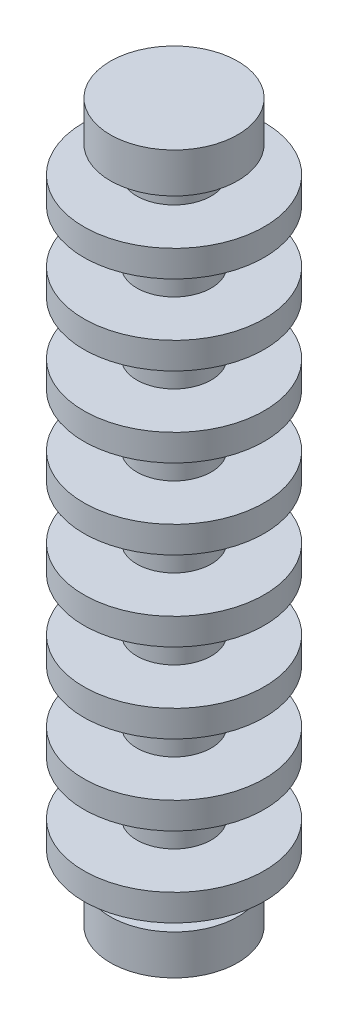
SolidWorks part; units mm, degrees
ref_plane "Front Plane" through (0, 0, 0) normal (0, 0, 1) x (1, 0, 0)
ref_plane "Top Plane" through (0, 0, 0) normal (0, 1, 0) x (1, 0, 0)
ref_plane "Right Plane" through (0, 0, 0) normal (1, 0, 0) x (0, 0, -1)
sketch "Sketch1" plane through (0, 0, 0) normal (0, 0, 1) x (1, 0, 0)
  line L0 (0, -24) -> (0, 24) construction
  line L1 (2.8, 24) -> (2.8, 22)
  line L2 (-20.9325, 24) -> (2.8, 24) construction
  line L3 (2.8, 18) -> (2.8, 16)
  line L4 (2.8, 16) -> (6.8, 16)
  line L5 (2.8, 22) -> (6.8, 22)
  line L6 (6.8, 22) -> (6.8, 20)
  line L7 (6.8, 20) -> (2.8, 20)
  line L8 (2.8, 20) -> (2.8, 18)
  line L9 (2.8, 24) -> (4.8, 24)
  line L10 (4.8, 24) -> (4.8, 27)
  line L11 (4.8, 27) -> (0, 27)
  line L12 (0, 0) -> (33.9437, 0) construction
  line L13 (6.8, 16) -> (6.8, 14)
  line L14 (6.8, 14) -> (2.8, 14)
  line L15 (2.8, 14) -> (2.8, 12)
  line L16 (0, 27) -> (0, -27)
  line L17 (4.8, -27) -> (0, -27)
  line L18 (4.8, -24) -> (4.8, -27)
  line L19 (2.8, -24) -> (4.8, -24)
  line L20 (2.8, 12) -> (2.8, 10)
  line L21 (2.8, 10) -> (6.8, 10)
  line L22 (6.8, 10) -> (6.8, 8)
  line L23 (6.8, 8) -> (2.8, 8)
  line L24 (2.8, 8) -> (2.8, 6)
  line L29 (2.8, 6) -> (2.8, 4)
  line L30 (2.8, 4) -> (6.8, 4)
  line L31 (6.8, 4) -> (6.8, 2)
  line L32 (6.8, 2) -> (2.8, 2)
  line L33 (2.8, 2) -> (2.8, 0)
  line L38 (2.8, 0) -> (2.8, -2)
  line L39 (2.8, -2) -> (6.8, -2)
  line L40 (6.8, -2) -> (6.8, -4)
  line L41 (6.8, -4) -> (2.8, -4)
  line L42 (2.8, -4) -> (2.8, -6)
  line L47 (2.8, -6) -> (2.8, -8)
  line L48 (2.8, -8) -> (6.8, -8)
  line L49 (6.8, -8) -> (6.8, -10)
  line L50 (6.8, -10) -> (2.8, -10)
  line L51 (2.8, -10) -> (2.8, -12)
  line L56 (2.8, -12) -> (2.8, -14)
  line L57 (2.8, -14) -> (6.8, -14)
  line L58 (6.8, -14) -> (6.8, -16)
  line L59 (6.8, -16) -> (2.8, -16)
  line L60 (2.8, -16) -> (2.8, -18)
  line L65 (2.8, -18) -> (2.8, -20)
  line L66 (2.8, -20) -> (6.8, -20)
  line L67 (6.8, -20) -> (6.8, -22)
  line L68 (6.8, -22) -> (2.8, -22)
  line L69 (2.8, -22) -> (2.8, -24)
  point P4 (0, 0)
  dimension "D1" = 48
  dimension "D2" = 2.8
  dimension "D3" = 4.8
  dimension "D4" = 3
  dimension "D5" = 2
  dimension "D6" = 2
  dimension "D7" = 2
  dimension "D11" = 4
  dimension "D12" = 8
revolve "Revolve1" add sketch "Sketch1" angle 360 about L16
